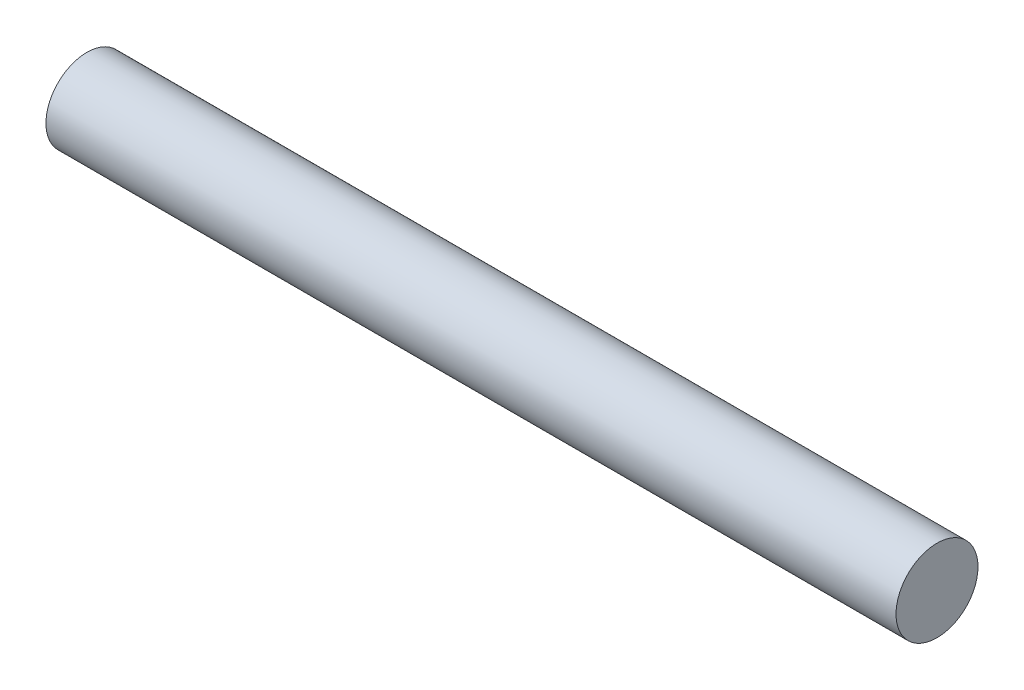
SolidWorks part; units mm, degrees
material "Custom Plastic"
ref_plane "X-Y Datum" through (0, 0, 0) normal (0, 0, 1) x (1, 0, 0)
ref_plane "X-Z Datum" through (0, 0, 0) normal (0, 1, 0) x (1, 0, 0)
ref_plane "Y-Z Datum" through (0, 0, 0) normal (1, 0, 0) x (0, 0, -1)
sketch3d "3DSketch1"
  line L0 (-169.1355, -97.75, 219.825) -> (-103.2905, -97.75, 219.825)
  circle A0 centre (-169.1355, -97.75, 219.825) radius 4.5 construction
  circle A3 centre (-103.2905, -97.75, 219.825) radius 4.5 construction
  point P4 (-164.6355, -97.75, 219.825)
  point P7 (-107.7905, -97.75, 219.825)
sweep "Sweep1" add path "3DSketch1" circular profile diameter 6.35 parameters "D3"=6.35
